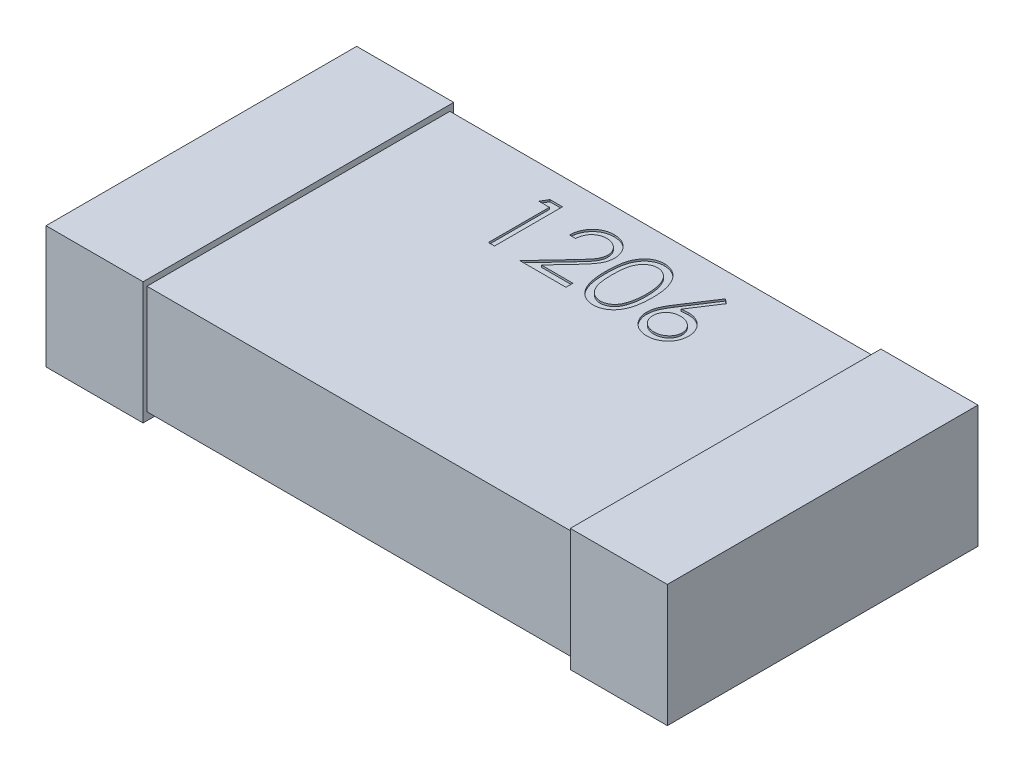
SolidWorks part; units mm, degrees
ref_plane "Front" through (0, 0, 0) normal (0, 0, 1) x (1, 0, 0)
ref_plane "Top" through (0, 0, 0) normal (0, 1, 0) x (1, 0, 0)
ref_plane "Right" through (0, 0, 0) normal (1, 0, 0) x (0, 0, -1)
sketch "Sketch1" plane through (0, 0, 0) normal (0, 1, 0) x (1, 0, 0)
  line L1 (0, 0) -> (0.5, 0)
  line L2 (0, 0) -> (0, 1.6)
  line L3 (0, 1.6) -> (0.5, 1.6)
  line L4 (0.5, 0) -> (0.5, 1.6)
  line L5 (2.7, 0) -> (3.2, 0)
  line L6 (2.7, 0) -> (2.7, 1.6)
  line L7 (2.7, 1.6) -> (3.2, 1.6)
  line L8 (3.2, 0) -> (3.2, 1.6)
  dimension "D1" = 0.5
  dimension "D2" = 0.5
  dimension "D3" = 1.6
  dimension "D4" = 1.6
  dimension "D5" = 3.2
extrude "Boss-Extrude1" add sketch "Sketch1" along normal blind 0.63
sketch "Sketch2" plane through (0.5, 0, 0) normal (1, 0, 0) x (0, 0, -1)
  line L2 (0.02, 0.04) -> (1.58, 0.04)
  line L3 (0.02, 0.04) -> (0.02, 0.6)
  line L4 (0.02, 0.6) -> (1.58, 0.6)
  line L5 (1.58, 0.04) -> (1.58, 0.6)
  line L6 (0, 0) -> (1.6, 0) construction
  line L7 (0, 0.63) -> (0, 0) construction
  dimension "D1" = 0.56
  dimension "D2" = 0.04
  dimension "D3" = 1.56
  dimension "D4" = 0.02
extrude "Boss-Extrude3" add sketch "Sketch2" along normal up to next contours L4 L5 L2 L3
sketch "Sketch6" plane through (0, 0.6, 0) normal (0, 1, 0) x (1, 0, 0)
  text T0 "1206" font "Century Gothic" height 0.35
extrude "Cut-Extrude1" cut sketch "Sketch6" against normal blind 0.01
